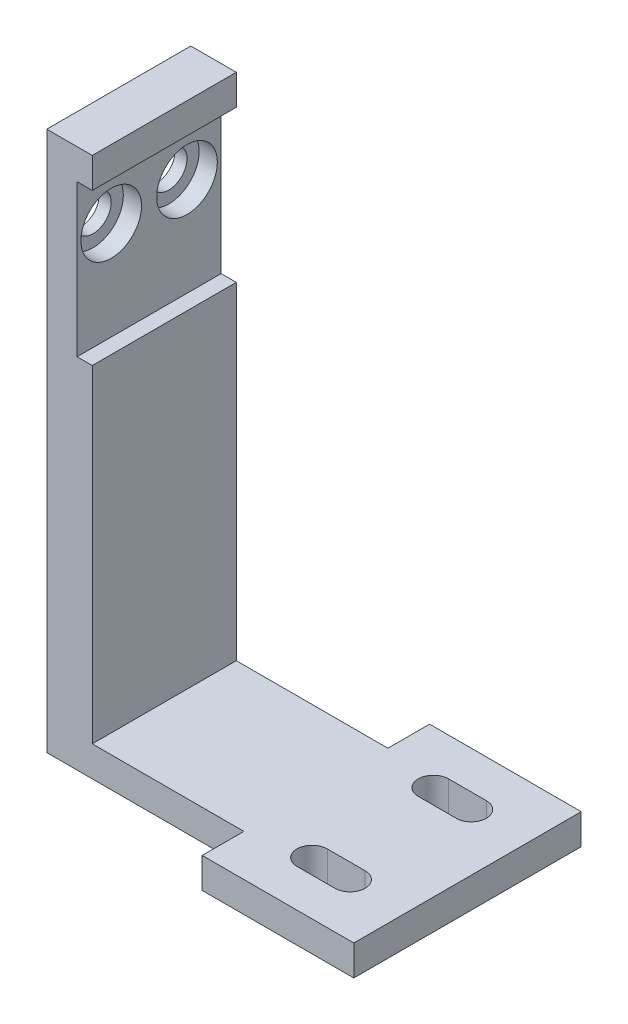
SolidWorks part; units mm, degrees
material "6061-T6 (SS)"
ref_plane "Front Plane" through (0, 0, 0) normal (0, 0, 1) x (1, 0, 0)
ref_plane "Top Plane" through (0, 0, 0) normal (0, 1, 0) x (1, 0, 0)
ref_plane "Right Plane" through (0, 0, 0) normal (1, 0, 0) x (0, 0, -1)
sketch "Sketch1" plane through (0, 0, 0) normal (0, 0, 1) x (1, 0, 0)
  line L0 (-15.4886, 20.5) -> (-17.5374, 20.5) construction
  line L9 (-17.5374, 15.5) -> (-17.5374, 25.5)
  line L10 (-19.5374, 0) -> (-19.5374, 27.5)
  line L11 (-19.5374, 27.5) -> (-16.5374, 27.5)
  line L12 (-16.5374, 27.5) -> (-16.5374, 25.5)
  line L17 (-12.4274, -6.11) -> (3.4626, -6.11)
  line L18 (3.4626, -6.11) -> (3.4626, -8.11)
  line L19 (3.4626, -8.11) -> (-11.4274, -8.11)
  line L20 (-17.5374, 25.5) -> (-16.5374, 25.5)
  line L21 (-17.5374, 15.5) -> (-16.5374, 15.5)
  line L22 (-16.5374, 15.5) -> (-16.5374, 12.5)
  line L23 (-19.5374, 0) -> (-19.5374, -8.11)
  line L24 (-19.5374, -8.11) -> (-11.4274, -8.11)
  line L25 (-16.5374, 12.5) -> (-16.5374, -6.11)
  line L26 (-16.5374, -6.11) -> (-12.4274, -6.11)
  line L29 (-12.4274, -6.11) -> (-10.0144, -6.11) construction
  point P15 (-17.5374, 20.5)
  point P21 (-12.4274, 0)
  dimension "D3" = 35.61
  dimension "D4" = 3
  dimension "D2" = 3
  dimension "D5" = 23
  dimension "D6" = 10
  dimension "D7" = 2
  dimension "D8" = 1
  dimension "D10" = 2
extrude "Boss-Extrude1" add sketch "Sketch1" along normal mid plane 9.5
sketch "Sketch2" plane through (-17.5374, 0, 0) normal (1, 0, 0) x (0, 0, -1)
  line L0 (-4.75, 20.5) -> (4.75, 20.5) construction
  line L1 (-4.75, 15.5) -> (-4.75, 25.5) construction
  line L2 (4.75, 15.5) -> (4.75, 25.5) construction
  line L3 (-4.75, 22) -> (4.75, 22) construction
  line L4 (0, 22) -> (0, 20.5) construction
  point P8 (-2.5, 22)
  point P11 (2.5, 22)
  dimension "D2" = 2.5
  dimension "D1" = 1.5
hole_wizard "M2 Clearance Hole1" positions "3DSketch1" profile "Sketch3" hole size "M2" standard "ANSI Metric" end condition through all
sketch3d "3DSketch1"
  point P0 (-17.5374, 22, 2.5)
  point P3 (-17.5374, 22, -2.5)
sketch "Sketch3" plane through (-17.5374, 22, 2.5) normal (0, 1, 0) x (0, 0, -1)
  line L0 (0, 0) -> (0, 2)
  line L1 (0, 2) -> (1.2, 2)
  line L2 (1.2, 2) -> (1.2, 0)
  line L5 (1.2, 0) -> (0, 0)
  line L11 (0, -6.35) -> (0, 107.95) construction
  dimension "Thru Hole Dia." = 2.4
  dimension "Thru Hole Depth" = 2
sketch "Sketch4" plane through (-17.5374, 0, 0) normal (1, 0, 0) x (0, 0, -1)
  circle A0 centre (-2.5, 22) radius 2
  circle A1 centre (2.5, 22) radius 2
  dimension "D1" = 4
  dimension "D2" = 4
extrude "Cut-Extrude1" cut sketch "Sketch4" against normal blind 1.2
sketch "Sketch5" plane through (0, -8.11, 0) normal (0, -1, 0) x (1, 0, 0)
  line L0 (3.4626, -7.5) -> (3.4626, 7.5)
  line L1 (3.4626, 4.75) -> (3.4626, -4.75) construction
  line L2 (3.4626, 7.5) -> (-6.5374, 7.5)
  line L3 (-6.5374, 7.5) -> (-6.5374, -7.5)
  line L4 (-6.5374, -7.5) -> (3.4626, -7.5)
  point P3 (3.4626, 0)
  dimension "D1" = 10
  dimension "D2" = 15
extrude "Boss-Extrude2" add sketch "Sketch5" against normal blind 2
sketch "Sketch6" plane through (0, -6.11, 0) normal (0, 1, 0) x (1, 0, 0)
  line L0 (3.4626, 0) -> (-6.5374, 0) construction
  line L1 (3.4626, 7.5) -> (3.4626, -7.5) construction
  line L2 (-0.2874, -4) -> (-2.7874, -4) construction
  line L3 (-1.5374, -7.5) -> (-1.5374, 7.5) construction
  line L4 (3.4626, -7.5) -> (-6.5374, -7.5) construction
  line L5 (-6.5374, 7.5) -> (3.4626, 7.5) construction
  line L6 (-0.2874, -5) -> (-2.7874, -5)
  line L7 (-0.2874, -3) -> (-2.7874, -3)
  line L8 (-0.2874, 4) -> (-2.7874, 4) construction
  line L9 (-0.2874, 5) -> (-2.7874, 5)
  line L10 (-0.2874, 3) -> (-2.7874, 3)
  arc A0 (-0.2874, -5) -> (-0.2874, -3) centre (-0.2874, -4) ccw
  arc A1 (-2.7874, -3) -> (-2.7874, -5) centre (-2.7874, -4) ccw
  arc A2 (-0.2874, 5) -> (-0.2874, 3) centre (-0.2874, 4) cw
  arc A3 (-2.7874, 3) -> (-2.7874, 5) centre (-2.7874, 4) cw
  point P12 (-1.5374, -4)
  point P13 (-1.5374, 0)
  point P14 (-1.5374, 4)
  point P15 (-1.5374, -4)
  point P23 (-1.5374, 4)
  dimension "D3" = 1
  dimension "D1" = 4
  dimension "D2" = 2.5
extrude "Cut-Extrude2" cut sketch "Sketch6" against normal up to surface (2 mm away) up to face at (-7.2874, -8.11, 0)
